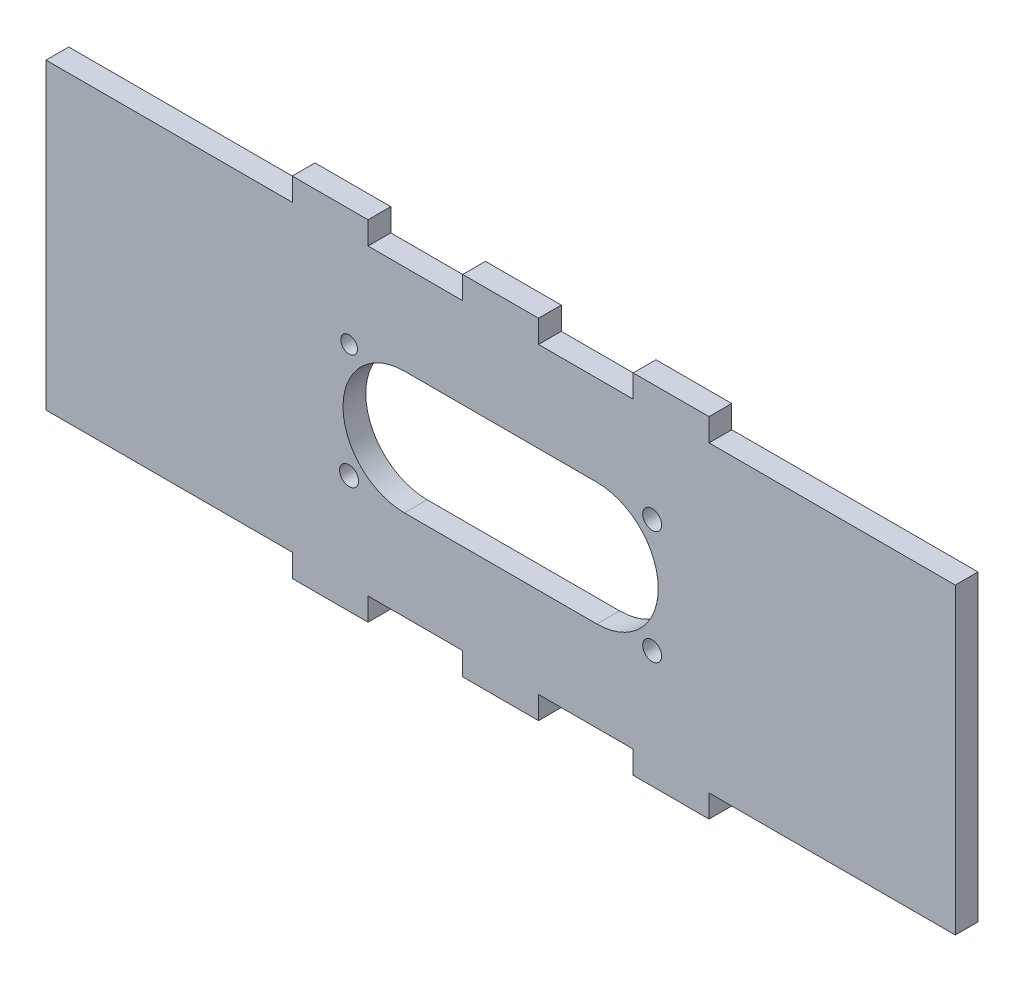
SolidWorks part; units mm, degrees
ref_plane "Front Plane" through (0, 0, 0) normal (0, 0, 1) x (1, 0, 0)
ref_plane "Top Plane" through (0, 0, 0) normal (0, 1, 0) x (1, 0, 0)
ref_plane "Right Plane" through (0, 0, 0) normal (1, 0, 0) x (0, 0, -1)
sketch "Sketch1" plane through (0, 0, 0) normal (0, 0, 1) x (1, 0, 0)
  line L0 (-60, 0) -> (60, 0) construction
  line L1 (-60, 20) -> (60, 20)
  line L2 (-60, 20) -> (-60, -20)
  line L3 (-60, -20) -> (60, -20)
  line L4 (60, 20) -> (60, -20)
  line L5 (-27.5, -23) -> (-17.5, -23)
  line L6 (-5, 20) -> (5, 20)
  line L7 (-5, 20) -> (-5, 23)
  line L8 (-5, 23) -> (5, 23)
  line L9 (5, 20) -> (5, 23)
  line L10 (17.5, 20) -> (27.5, 20)
  line L11 (17.5, 20) -> (17.5, 23)
  line L12 (17.5, 23) -> (27.5, 23)
  line L13 (27.5, 20) -> (27.5, 23)
  line L14 (-27.5, 20) -> (-17.5, 20)
  line L15 (-27.5, 20) -> (-27.5, 23)
  line L16 (-27.5, 23) -> (-17.5, 23)
  line L17 (-17.5, 20) -> (-17.5, 23)
  line L18 (-17.5, -20) -> (-17.5, -23)
  line L19 (-27.5, -20) -> (-17.5, -20)
  line L20 (-27.5, -20) -> (-27.5, -23)
  line L21 (-5, -23) -> (5, -23)
  line L22 (5, -20) -> (5, -23)
  line L23 (-5, -20) -> (5, -20)
  line L24 (-5, -20) -> (-5, -23)
  line L25 (17.5, -23) -> (27.5, -23)
  line L26 (27.5, -20) -> (27.5, -23)
  line L27 (17.5, -20) -> (27.5, -20)
  line L28 (17.5, -20) -> (17.5, -23)
  point P4 (0, 20)
  point P6 (-60, 0)
  point P21 (0, 23)
  dimension "D1" = 120
  dimension "D2" = 40
  dimension "D3" = 3
  dimension "D4" = 10
  dimension "D5" = 17.5
  dimension "D6" = 17.5
extrude "Boss-Extrude1" add sketch "Sketch1" along normal blind 3 contours L2 L0 L4 L1 | L0 L2 L3 L4 | L1 L17 L16 L15 | L1 L9 L8 L7 | L1 L13 L12 L11 | L3 L28 L25 L26 | L3 L24 L21 L22 | L3 L20 L5 L18
sketch "Sketch2" plane through (0, 0, 3) normal (0, 0, 1) x (1, 0, 0)
  point P0 (-22.5, 0)
  point P1 (0, 0)
  circle B0 centre (-20, 7.5) radius 1.1
  circle B1 centre (-20, -7.5) radius 1.25
  circle B2 centre (20, -7.5) radius 1.25
  circle B3 centre (20, 7.5) radius 1.25
  circle B4 centre (-12.7, 0) radius 8.1
  circle B5 centre (12.7, 0) radius 8.1
sketch_block_instance "Block4-1"
sketch_block "Block4" parameters "D3"=2.2, "D6"=16.2, "D1"=45, "D2"=20, "D4"=2.5, "D5"=2.5, "D7"=25.4
extrude "Cut-Extrude1" cut sketch "Sketch2" against normal through all
sketch "Sketch3" plane through (0, 0, 3) normal (0, 0, 1) x (1, 0, 0)
  line L9 (-12.7, 8.1) -> (12.7, 8.1)
  line L10 (-12.7, 8.1) -> (-12.7, -8.1)
  line L11 (-12.7, -8.1) -> (12.7, -8.1)
  line L12 (12.7, 8.1) -> (12.7, -8.1)
  circle A0 centre (-12.7, 0) radius 8.1 construction
  circle A1 centre (12.7, 0) radius 8.1 construction
  point P8 (12.7, 0)
extrude "Cut-Extrude2" cut sketch "Sketch3" against normal through all
